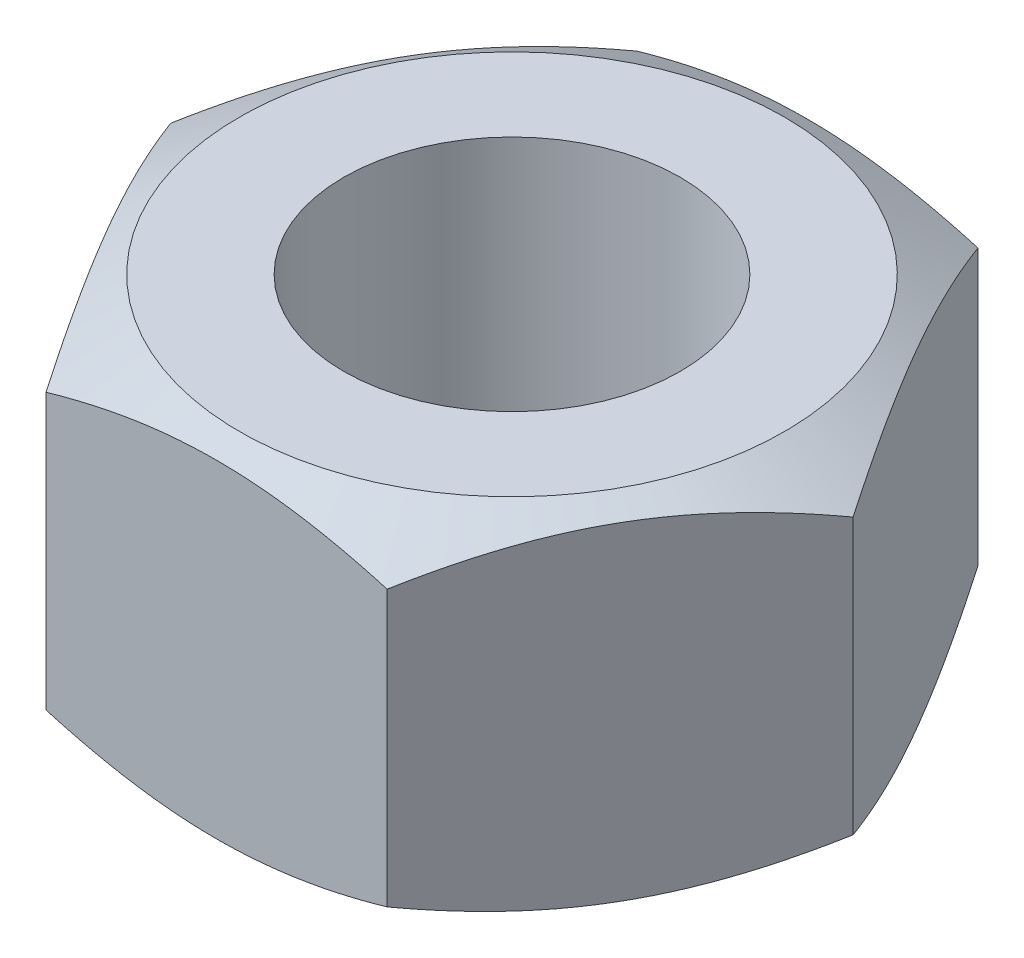
SolidWorks part; units mm, degrees
material "Wrought Stainless Steel"
ref_plane "Front Plane" through (0, 0, 0) normal (0, 0, 1) x (1, 0, 0)
ref_plane "Top Plane" through (0, 0, 0) normal (0, 1, 0) x (1, 0, 0)
ref_plane "Right Plane" through (0, 0, 0) normal (1, 0, 0) x (0, 0, -1)
sketch "Sketch1" plane through (0, 0, 0) normal (0, 1, 0) x (1, 0, 0)
  line L1 (10.3923, 0) -> (5.1962, 9)
  line L2 (5.1962, 9) -> (-5.1962, 9)
  line L3 (-5.1962, 9) -> (-10.3923, 0)
  line L4 (-10.3923, 0) -> (-5.1962, -9)
  line L5 (-5.1962, -9) -> (5.1962, -9)
  line L6 (5.1962, -9) -> (10.3923, 0)
  circle A0 centre (0, 0) radius 9 construction
  circle A1 centre (0, 0) radius 5.125
  dimension "MD" = 10.25
  dimension "S" = 18
extrude "Extrude1" add sketch "Sketch1" along normal blind 10.8
cosmetic thread "Cosmetic Thread1" parameters "M"=12
sketch "Sketch2" plane through (0, 0, 0) normal (0, 0, 1) x (1, 0, 0)
  line L0 (0, 0) -> (0, 16.1977) construction
  line L1 (-8.3, 10.8) -> (-10.3923, 9.592)
  line L2 (-10.3923, 10.8) -> (-5.1962, 10.8) construction
  line L3 (-10.3923, 10.8) -> (-10.3923, 0) construction
  line L4 (-10.3923, 1.208) -> (-8.3, 0)
  line L6 (-10.3923, 0) -> (-5.1962, 0) construction
  line L7 (-10.3923, 9.592) -> (-10.3923, 10.8)
  line L8 (-10.3923, 10.8) -> (-8.3, 10.8)
  line L9 (-10.3923, 1.208) -> (-10.3923, 0)
  line L10 (-10.3923, 0) -> (-8.3, 0)
  dimension "DW" = 16.6
  dimension "D2" = 30
  dimension "D3" = 30
revolve "Cut-Revolve1" cut sketch "Sketch2" angle 360 about L0
